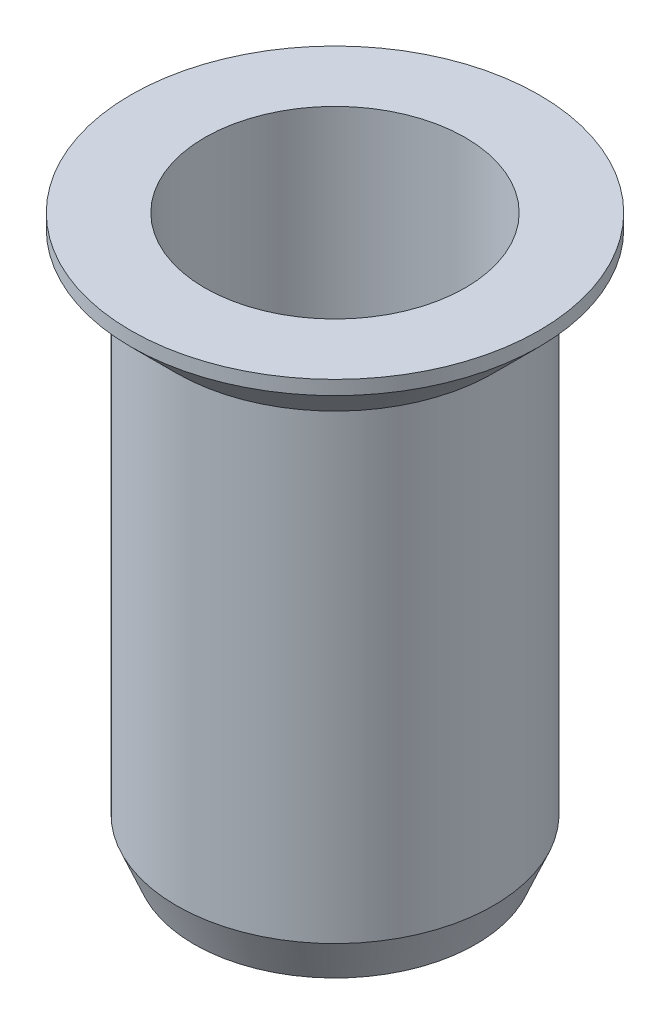
SolidWorks part; units mm, degrees
material "Acier non allié"
ref_plane "Plan de face" through (0, 0, 0) normal (0, 0, 1) x (1, 0, 0)
ref_plane "Plan de dessus" through (0, 0, 0) normal (0, 1, 0) x (1, 0, 0)
ref_plane "Plan de droite" through (0, 0, 0) normal (1, 0, 0) x (0, 0, -1)
sketch "Esquisse1" plane through (0, 0, 0) normal (0, 0, 1) x (1, 0, 0)
  line L0 (0, 0) -> (0, 47.77) construction
  line L1 (0, 0) -> (3.7, 0) construction
  line L2 (3.7, 9) -> (3.7, 16)
  line L3 (3.7, 16) -> (5.8, 16)
  line L4 (5.8, 16) -> (5.8, 15.6)
  line L5 (5.8, 15.6) -> (4.5, 14.3)
  line L6 (4.5, 14.3) -> (4.5, 1.2)
  line L7 (4.5, 1.2) -> (4, 0)
  line L8 (4, 0) -> (3.7, 0)
  line L10 (3.7, 0) -> (3, 0)
  line L12 (3.7, 9) -> (3, 9)
  line L13 (3, 0) -> (3, 9)
  dimension "D1" = 3.7
  dimension "D2" = 4
  dimension "D3" = 4.5
  dimension "D4" = 1.2
  dimension "D5" = 16
  dimension "D6" = 0.4
  dimension "D7" = 135
  dimension "D8" = 3
  dimension "D9" = 9
  dimension "D10" = 5.8
  dimension "D11" = 1.3
revolve "Révolution1" add sketch "Esquisse1" angle 360 about L0
